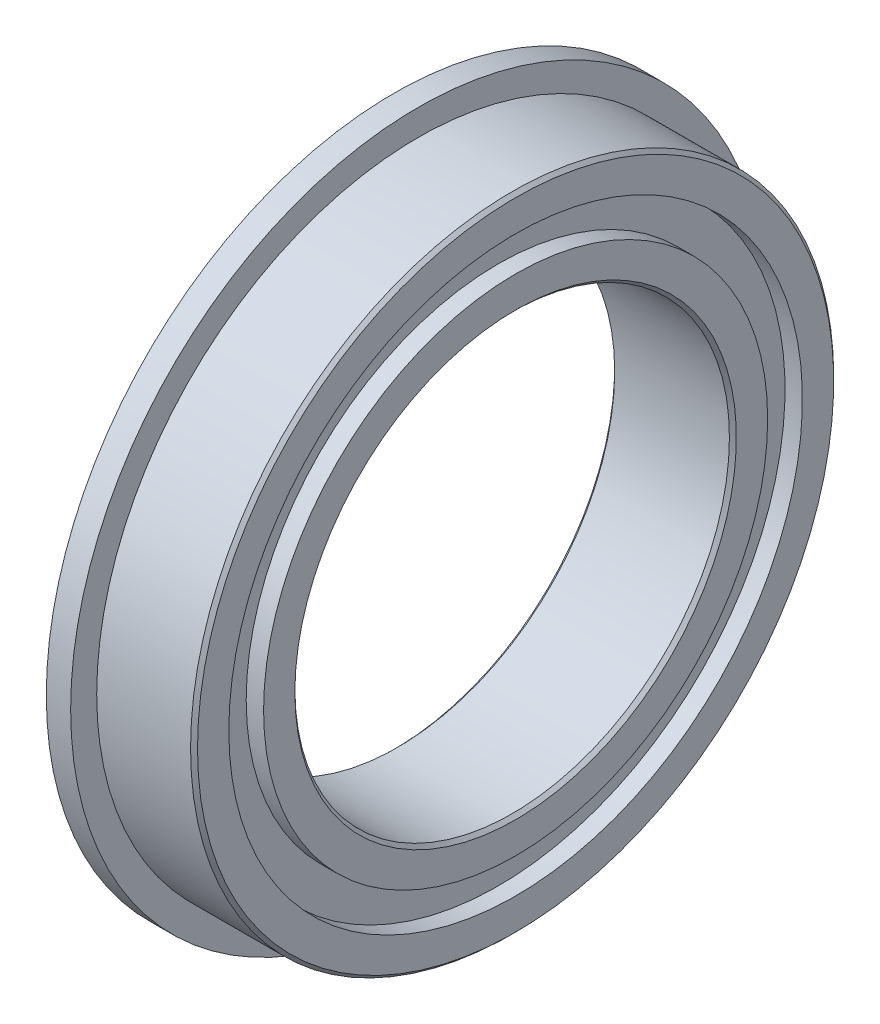
SolidWorks part; units mm, degrees
ref_plane "Front Plane" through (0, 0, 0) normal (0, 0, 1) x (1, 0, 0)
ref_plane "Top Plane" through (0, 0, 0) normal (0, 1, 0) x (1, 0, 0)
ref_plane "Right Plane" through (0, 0, 0) normal (1, 0, 0) x (0, 0, -1)
sketch "Sketch2" plane through (0, 0, 0) normal (0, 1, 0) x (1, 0, 0)
  line L0 (0, 12.7) -> (0, 14.5)
  line L1 (1.4, 18.5) -> (6.8, 18.5)
  line L2 (7, 18.3) -> (7, 16.5)
  line L3 (6.8, 12.5) -> (0.2, 12.5)
  line L4 (7, 14.5) -> (6, 14.5)
  line L5 (6, 14.5) -> (6, 16.5)
  line L6 (6, 16.5) -> (7, 16.5)
  line L7 (0, 12.5) -> (0, 0) construction
  line L8 (0, 0) -> (7.5948, 0) construction
  line L9 (7, 14.5) -> (7, 12.7)
  line L10 (3.5, 18.5) -> (3.5, 12.5) construction
  line L11 (0, 14.5) -> (1, 14.5)
  line L12 (1, 16.5) -> (0, 16.5)
  line L13 (1, 14.5) -> (1, 16.5)
  line L14 (0, 16.5) -> (0, 20)
  line L15 (6.8, 18.5) -> (7, 18.3)
  line L17 (7, 12.7) -> (6.8, 12.5)
  line L18 (0.2, 12.5) -> (0, 12.7)
  line L19 (0, 20) -> (1.4, 20)
  line L20 (1.4, 20) -> (1.4, 18.5)
  point P1 (0, 18.5)
  point P4 (7, 18.5)
  point P5 (7, 12.5)
  dimension "D1" = 18.5
  dimension "D2" = 12.5
  dimension "D3" = 2
  dimension "D4" = 2
  dimension "D5" = 1
  dimension "D6" = 7
  dimension "D7" = 1.4
  dimension "D8" = 1.5
revolve "Revolve1" add sketch "Sketch2" angle 360 about L8
